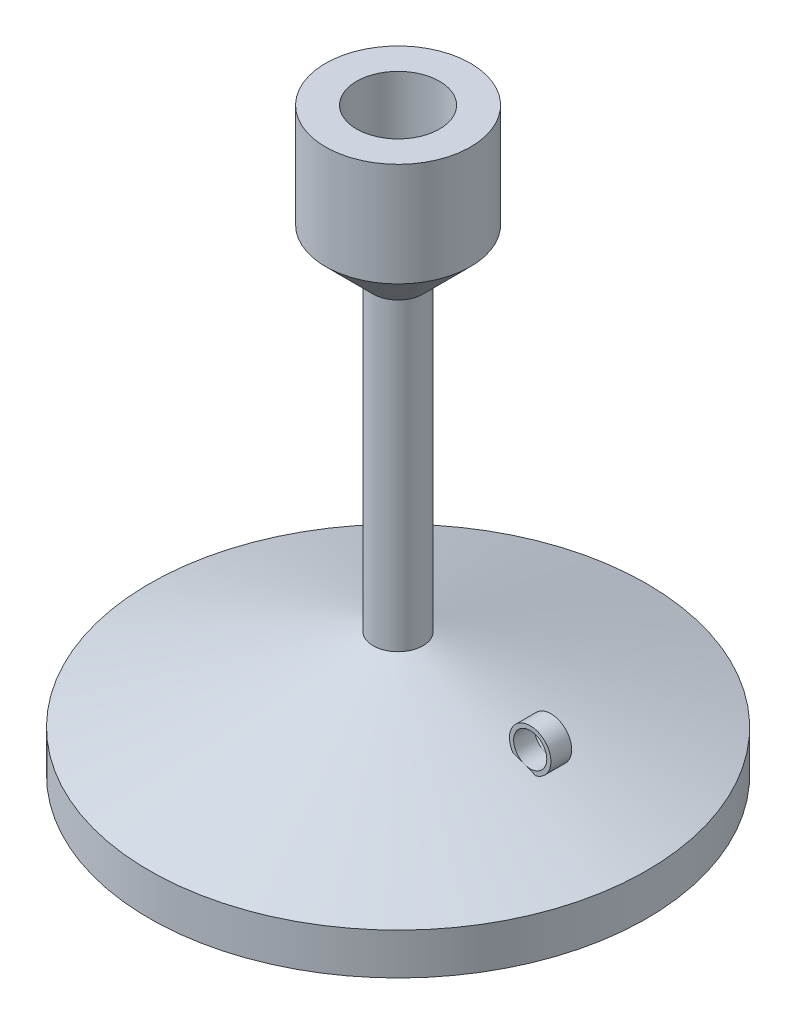
SolidWorks part; units mm, degrees
ref_plane "Front Plane" through (0, 0, 0) normal (0, 0, 1) x (1, 0, 0)
ref_plane "Top Plane" through (0, 0, 0) normal (0, 1, 0) x (1, 0, 0)
ref_plane "Right Plane" through (0, 0, 0) normal (1, 0, 0) x (0, 0, -1)
sketch "Sketch2" plane through (0, 0, 0) normal (0, 0, 1) x (1, 0, 0)
  line L0 (0, 0) -> (0, 140) construction
  line L1 (0, 120) -> (-10, 120)
  line L2 (-10, 120) -> (-10, 140)
  line L3 (-10, 140) -> (-17.5, 140)
  line L4 (-17.5, 140) -> (-17.5, 115)
  line L5 (-17.5, 115) -> (-6, 103.5)
  line L6 (-6, 103.5) -> (-6, 30)
  line L7 (-6, 30) -> (-60, 10)
  line L8 (-60, 10) -> (-60, 0)
  line L9 (-60, 0) -> (0, 0)
  line L10 (0, 0) -> (0, 120)
  point P4 (0, 0)
  point P7 (-6.5829, 57.8743)
  dimension "D1" = 140
  dimension "D2" = 20
  dimension "D3" = 35
  dimension "D4" = 45
  dimension "D5" = 12
  dimension "D6" = 10
  dimension "D7" = 30
  dimension "D8" = 20
  dimension "D9" = 25
  dimension "D10" = 120
revolve "Revolve1" add sketch "Sketch2" angle 360 about L0
sketch "Sketch3" plane through (0, 0, 0) normal (0, 0, 1) x (1, 0, 0)
  line L0 (60, 10) -> (6, 30) construction
  line L1 (60, 10) -> (6, 30) construction
  line L2 (33, 20) -> (34.3893, 23.751) construction
  circle A0 centre (34.3893, 23.751) radius 5
  circle A1 centre (34.3893, 23.751) radius 4
  dimension "D2" = 10
  dimension "D1" = 4
  dimension "D3" = 1
extrude "Boss-Extrude1" add sketch "Sketch3" along normal mid plane 5
